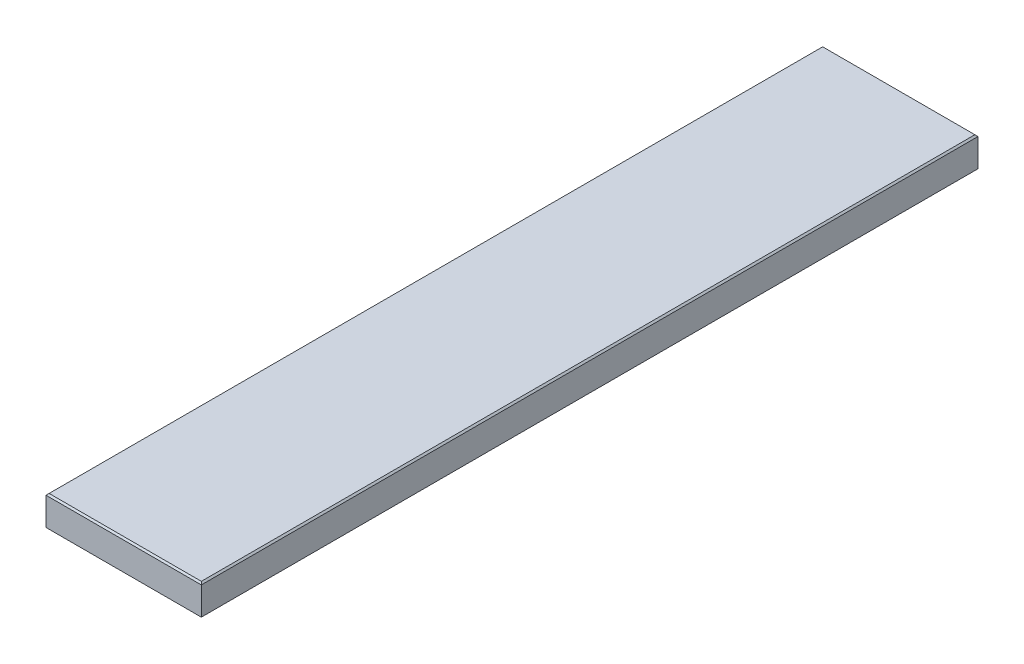
SolidWorks part; units mm, degrees
ref_plane "前视基准面" through (0, 0, 0) normal (0, 0, 1) x (1, 0, 0)
ref_plane "上视基准面" through (0, 0, 0) normal (0, 1, 0) x (1, 0, 0)
ref_plane "右视基准面" through (0, 0, 0) normal (1, 0, 0) x (0, 0, -1)
other "Configuration Table"
sketch "草图1" plane through (0, 0, 0) normal (0, 1, 0) x (1, 0, 0)
  line L1 (0, 0) -> (20, 0)
  line L2 (0, 0) -> (0, 100)
  line L3 (0, 100) -> (20, 100)
  line L4 (20, 0) -> (20, 100)
  dimension "D1" = 20
  dimension "D2" = 100
extrude "凸台-拉伸1" add sketch "草图1" along normal blind 4
chamfer "倒角1" distance 0.2 angle 45 8 edges at (10, 0, 0) (20, 0, -50) (10, 0, -100) (0, 0, -50) (10, 4, -100) (20, 4, -50) (10, 4, 0) (0, 4, -50)
